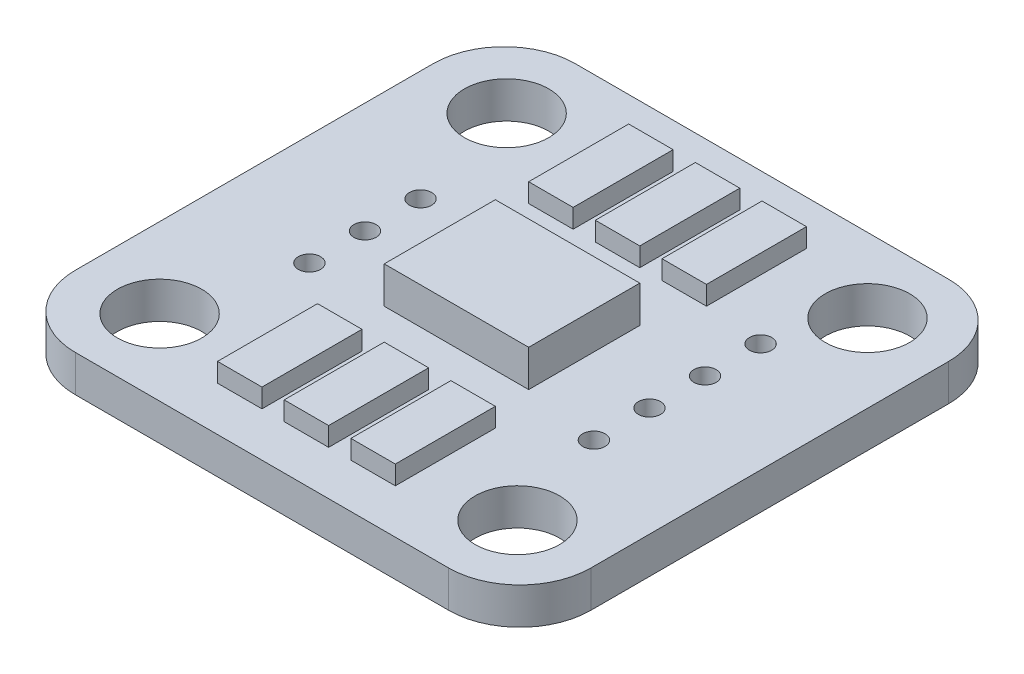
SolidWorks part; units mm, degrees
material "Custom Plastic"
ref_plane "Front Plane" through (0, 0, 0) normal (0, 0, 1) x (1, 0, 0)
ref_plane "Top Plane" through (0, 0, 0) normal (0, 1, 0) x (1, 0, 0)
ref_plane "Right Plane" through (0, 0, 0) normal (1, 0, 0) x (0, 0, -1)
sketch "Sketch1" plane through (0, 0, 0) normal (0, 1, 0) x (1, 0, 0)
  line L1 (-8.4, -11.25) -> (8.4, -11.25)
  line L2 (-11.6, -8.05) -> (-11.6, 8.05)
  line L3 (-8.4, 11.25) -> (8.4, 11.25)
  line L4 (11.6, -8.05) -> (11.6, 8.05)
  line L5 (-11.6, -11.25) -> (11.6, 11.25) construction
  line L6 (-11.6, 11.25) -> (11.6, -11.25) construction
  line L7 (-8.0152, -7.8409) -> (8.0848, -7.8409) construction
  line L8 (-8.0152, -7.8409) -> (-8.0152, 7.7733) construction
  line L10 (8.0848, -7.8409) -> (8.0848, 7.9091) construction
  line L11 (-8.0152, -7.8409) -> (8.0848, 7.9091) construction
  line L12 (-8.0152, 7.7733) -> (8.0848, -7.8409) construction
  circle A0 centre (-8.0152, 7.7733) radius 1.9
  circle A1 centre (8.0848, 7.9091) radius 1.9
  circle A2 centre (8.0848, -7.8409) radius 1.9
  circle A3 centre (-8.0152, -7.8409) radius 1.9
  arc A4 (-8.4, -11.25) -> (-11.6, -8.05) centre (-8.4, -8.05) cw
  arc A5 (8.4, -11.25) -> (11.6, -8.05) centre (8.4, -8.05) ccw
  arc A6 (8.4, 11.25) -> (11.6, 8.05) centre (8.4, 8.05) cw
  arc A7 (-11.6, 8.05) -> (-8.4, 11.25) centre (-8.4, 8.05) cw
  point P0 (0, 0)
  point P15 (0, 0)
  dimension "D5" = 3.8
  dimension "D6" = 3.2
  dimension "D1" = 23.2
  dimension "D2" = 22.5
  dimension "D3" = 15.75
  dimension "D4" = 16.1
extrude "Boss-Extrude1" add sketch "Sketch1" along normal blind 1.65
sketch "Sketch3" plane through (0, 1.65, 0) normal (0, 1, 0) x (1, 0, 0)
  line L0 (0, 11.25) -> (0, -11.25) construction
  line L1 (8.4, 11.25) -> (-8.4, 11.25) construction
  line L2 (-8.4, -11.25) -> (8.4, -11.25) construction
  line L3 (2, 4.75) -> (4, 4.75)
  line L4 (-1, 4.75) -> (1, 4.75)
  line L5 (-1, 4.75) -> (-1, 9.25)
  line L6 (-1, 9.25) -> (1, 9.25)
  line L7 (1, 4.75) -> (1, 9.25)
  line L8 (-1, 4.75) -> (1, 9.25) construction
  line L9 (-1, 9.25) -> (1, 4.75) construction
  line L10 (2, 4.75) -> (2, 9.25)
  line L11 (2, 9.25) -> (4, 9.25)
  line L12 (4, 4.75) -> (4, 9.25)
  line L13 (2, 4.75) -> (4, 9.25) construction
  line L14 (2, 9.25) -> (4, 4.75) construction
  line L15 (-2, 9.25) -> (-4, 4.75) construction
  line L16 (-2, 4.75) -> (-4, 9.25) construction
  line L17 (-4, 4.75) -> (-4, 9.25)
  line L18 (-2, 9.25) -> (-4, 9.25)
  line L19 (-2, 4.75) -> (-2, 9.25)
  line L20 (-2, 4.75) -> (-4, 4.75)
  line L21 (-11.6, 0) -> (11.6, 0) construction
  line L22 (-11.6, 8.05) -> (-11.6, -8.05) construction
  line L23 (11.6, -8.05) -> (11.6, 8.05) construction
  line L24 (-2, -4.75) -> (-4, -9.25) construction
  line L25 (-2, -9.25) -> (-4, -4.75) construction
  line L26 (2, -9.25) -> (4, -4.75) construction
  line L27 (2, -4.75) -> (4, -9.25) construction
  line L28 (-1, -9.25) -> (1, -4.75) construction
  line L29 (-1, -4.75) -> (1, -9.25) construction
  line L30 (-2, -4.75) -> (-4, -4.75)
  line L31 (-2, -4.75) -> (-2, -9.25)
  line L32 (-2, -9.25) -> (-4, -9.25)
  line L33 (-4, -4.75) -> (-4, -9.25)
  line L34 (4, -4.75) -> (4, -9.25)
  line L35 (2, -9.25) -> (4, -9.25)
  line L36 (2, -4.75) -> (2, -9.25)
  line L37 (1, -4.75) -> (1, -9.25)
  line L38 (-1, -9.25) -> (1, -9.25)
  line L39 (-1, -4.75) -> (-1, -9.25)
  line L40 (-1, -4.75) -> (1, -4.75)
  line L41 (2, -4.75) -> (4, -4.75)
  point P6 (0, 7)
  point P11 (3, 7)
  point P20 (-3, 7)
  point P39 (-3, -7)
  point P40 (3, -7)
  point P41 (0, -7)
  dimension "D1" = 2
  dimension "D2" = 4.5
  dimension "D3" = 2
  dimension "D5" = 6
  dimension "D4" = 2
extrude "Boss-Extrude2" add sketch "Sketch3" along normal offset from surface (0.85 mm away) 2.5 contours L20 L19 L18 L17 | L4 L7 L6 L5 | L3 L12 L11 L10 | L41 L36 L35 L34 | L40 L39 L38 L37 | L30 L33 L32 L31 up to face at (8.0848, 0, 9.7409)
sketch "Sketch4" plane through (0, 1.65, 0) normal (0, 1, 0) x (1, 0, 0)
  line L1 (-3.25, -2.5) -> (3.25, -2.5)
  line L2 (-3.25, -2.5) -> (-3.25, 2.5)
  line L3 (-3.25, 2.5) -> (3.25, 2.5)
  line L4 (3.25, -2.5) -> (3.25, 2.5)
  line L5 (-3.25, -2.5) -> (3.25, 2.5) construction
  line L6 (-3.25, 2.5) -> (3.25, -2.5) construction
  point P0 (0, 0)
  dimension "D1" = 6.5
  dimension "D2" = 5
extrude "Boss-Extrude3" add sketch "Sketch4" along normal offset from surface (1.65 mm away) 3.3 up to face at (8.0848, 0, 9.7409)
sketch "Sketch5" plane through (0, 1.65, 0) normal (0, 1, 0) x (1, 0, 0)
  line L0 (6.6848, 4.5) -> (6.6848, 2) construction
  line L1 (6.6848, 2) -> (6.6848, -0.5) construction
  line L2 (6.6848, -0.5) -> (6.6848, -3) construction
  line L3 (-6.6152, 2.5) -> (-6.6152, 0) construction
  line L4 (-6.6152, 0) -> (-6.6152, -2.5) construction
  line L5 (6.6848, 2.5) -> (3.25, 2.5) construction
  line L6 (-6.1152, 7.7733) -> (-6.1152, -7.8409) construction
  line L7 (6.1848, 7.9091) -> (6.1848, -7.8409) construction
  line L8 (8.4, 11.25) -> (-8.4, 11.25) construction
  circle A0 centre (-6.6152, 0) radius 0.5
  circle A1 centre (-6.6152, 2.5) radius 0.5
  circle A2 centre (-6.6152, -2.5) radius 0.5
  circle A3 centre (6.6848, 4.5) radius 0.5
  circle A4 centre (6.6848, 2) radius 0.5
  circle A5 centre (6.6848, -0.5) radius 0.5
  circle A6 centre (6.6848, -3) radius 0.5
  circle A7 centre (-8.0152, 7.7733) radius 1.9 construction
  circle A8 centre (-8.0152, -7.8409) radius 1.9 construction
  circle A9 centre (8.0848, 7.9091) radius 1.9 construction
  circle A10 centre (8.0848, -7.8409) radius 1.9 construction
  dimension "D2" = 1
  dimension "D1" = 2.5
extrude "Cut-Extrude1" cut sketch "Sketch5" against normal through all
